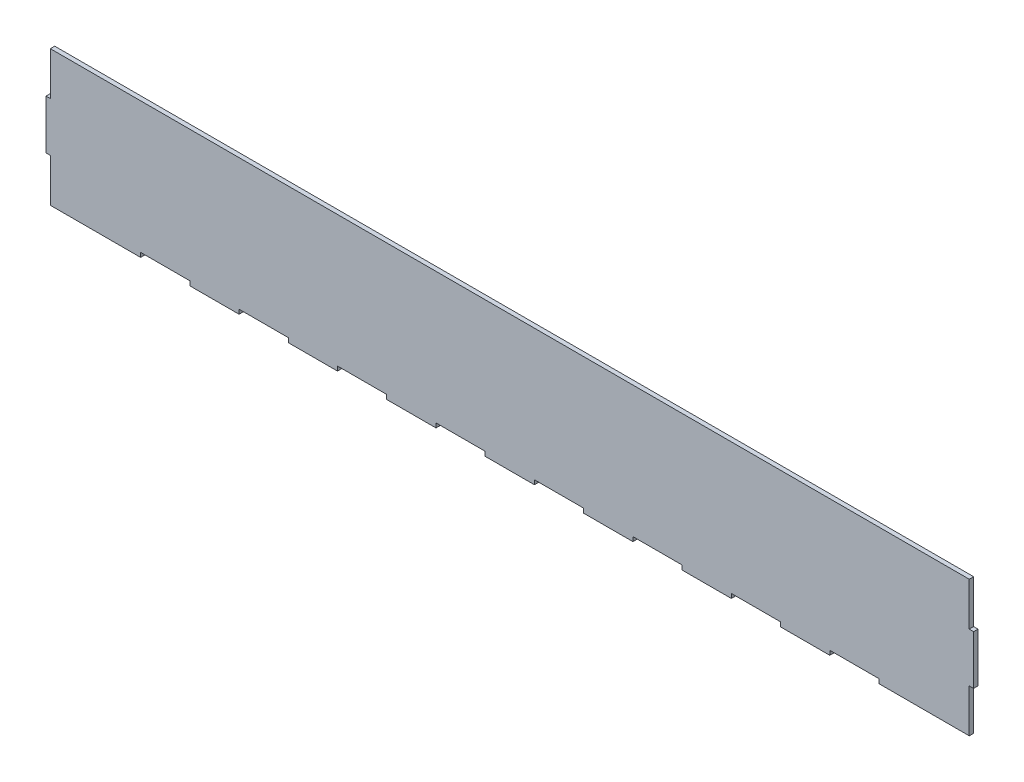
SolidWorks part; units mm, degrees
ref_plane "Front Plane" through (0, 0, 0) normal (0, 0, 1) x (1, 0, 0)
ref_plane "Top Plane" through (0, 0, 0) normal (0, 1, 0) x (1, 0, 0)
ref_plane "Right Plane" through (0, 0, 0) normal (1, 0, 0) x (0, 0, -1)
sketch "Model" plane through (0, 0, 0) normal (0, 0, 1) x (1, 0, 0)
  line L0 (642, 96) -> (642, 66.375)
  line L1 (642, 66.375) -> (639, 66.375)
  line L2 (639, 66.375) -> (639, 32.625)
  line L3 (639, 32.625) -> (642, 32.625)
  line L4 (642, 32.625) -> (642, 3)
  line L5 (642, 3) -> (703.875, 3)
  line L6 (703.875, 3) -> (703.875, 6)
  line L7 (703.875, 6) -> (737.625, 6)
  line L8 (737.625, 6) -> (737.625, 3)
  line L9 (737.625, 3) -> (771.375, 3)
  line L10 (771.375, 3) -> (771.375, 6)
  line L11 (771.375, 6) -> (805.125, 6)
  line L12 (805.125, 6) -> (805.125, 3)
  line L13 (805.125, 3) -> (838.875, 3)
  line L14 (838.875, 3) -> (838.875, 6)
  line L15 (838.875, 6) -> (872.625, 6)
  line L16 (872.625, 6) -> (872.625, 3)
  line L17 (872.625, 3) -> (906.375, 3)
  line L18 (906.375, 3) -> (906.375, 6)
  line L19 (906.375, 6) -> (940.125, 6)
  line L20 (940.125, 6) -> (940.125, 3)
  line L21 (940.125, 3) -> (973.875, 3)
  line L22 (973.875, 3) -> (973.875, 6)
  line L23 (973.875, 6) -> (1007.625, 6)
  line L24 (1007.625, 6) -> (1007.625, 3)
  line L25 (1007.625, 3) -> (1041.375, 3)
  line L26 (1041.375, 3) -> (1041.375, 6)
  line L27 (1041.375, 6) -> (1075.125, 6)
  line L28 (1075.125, 6) -> (1075.125, 3)
  line L29 (1075.125, 3) -> (1108.875, 3)
  line L30 (1108.875, 3) -> (1108.875, 6)
  line L31 (1108.875, 6) -> (1142.625, 6)
  line L32 (1142.625, 6) -> (1142.625, 3)
  line L33 (1142.625, 3) -> (1176.375, 3)
  line L34 (1176.375, 3) -> (1176.375, 6)
  line L35 (1176.375, 6) -> (1210.125, 6)
  line L36 (1210.125, 6) -> (1210.125, 3)
  line L37 (1210.125, 3) -> (1243.875, 3)
  line L38 (1243.875, 3) -> (1272, 3)
  line L39 (1272, 3) -> (1272, 32.625)
  line L40 (1272, 32.625) -> (1275, 32.625)
  line L41 (1275, 32.625) -> (1275, 66.375)
  line L42 (1275, 66.375) -> (1272, 66.375)
  line L43 (1272, 66.375) -> (1272, 96)
  line L44 (1272, 96) -> (642, 96)
extrude "Boss-Extrude1" add sketch "Model" along normal blind 3
